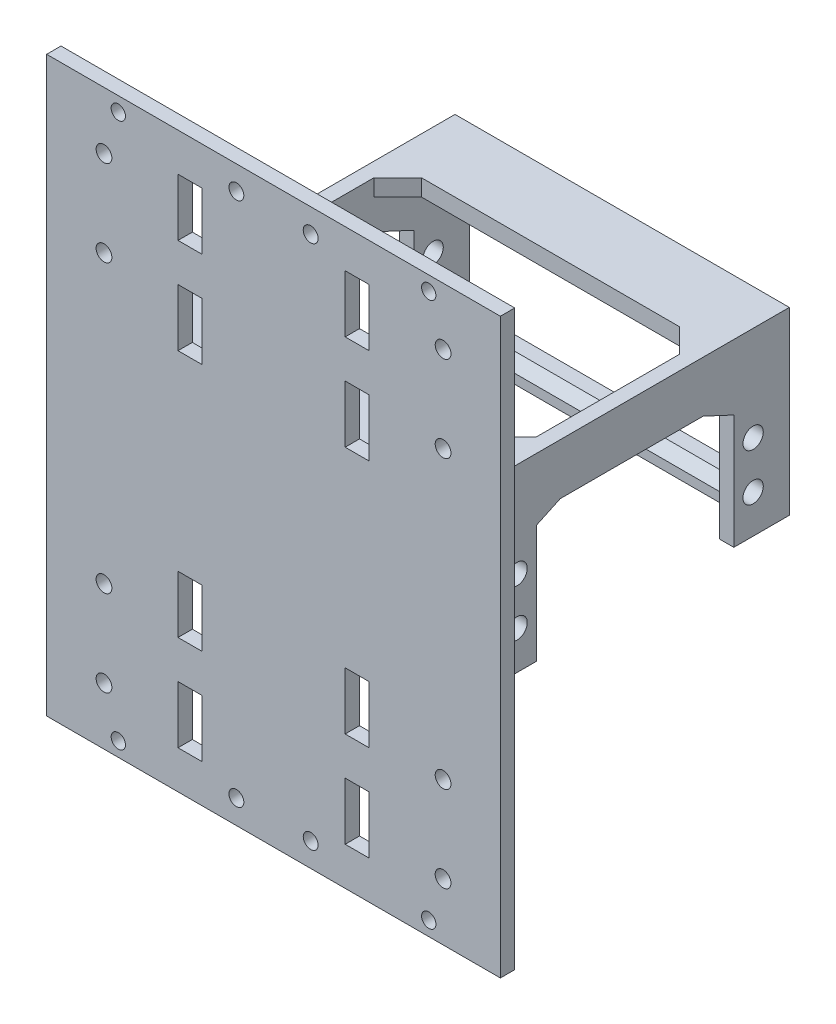
SolidWorks part; units mm, degrees
other "标注1"
sketch "草图14" plane through (-90, -59.2208, -73) normal (-0.775, -0.2253, -0.5905) x (0.6262, -0.4, -0.6693)
ref_plane "前视基准面" through (0, 0, 0) normal (0, 0, 1) x (1, 0, 0)
ref_plane "上视基准面" through (0, 0, 0) normal (0, 1, 0) x (1, 0, 0)
ref_plane "右视基准面" through (0, 0, 0) normal (1, 0, 0) x (0, 0, -1)
sketch "草图1" plane through (0, 0, 0) normal (0, 0, 1) x (1, 0, 0)
  line L0 (-47.5, 0) -> (47.5, 0) construction
  line L1 (-47.5, 60) -> (47.5, 60)
  line L2 (-47.5, 60) -> (-47.5, -60)
  line L3 (-47.5, -60) -> (47.5, -60)
  line L4 (47.5, 60) -> (47.5, -60)
  line L5 (0, 60) -> (0, -60) construction
  point P8 (0, 0)
  dimension "D1" = 120
  dimension "D2" = 95
extrude "凸台-拉伸1" add sketch "草图1" along normal blind 3 contours L2 L1 L4 L3
sketch "草图2" plane through (0, 0, 0) normal (0, 0, -1) x (-1, 0, 0)
  line L0 (-47.5, 0) -> (47.5, 0) construction
  line L1 (-47.5, 60) -> (-47.5, -60) construction
  line L2 (47.5, 60) -> (47.5, -60) construction
  line L3 (0, 60) -> (0, -60) construction
  line L4 (47.5, 60) -> (-47.5, 60) construction
  line L5 (47.5, -60) -> (-47.5, -60) construction
  line L6 (-35, -18.85) -> (-32, -18.85)
  line L7 (-35, 0) -> (-32, 0)
  line L8 (-35, -18.85) -> (-35, 18.85)
  line L9 (-35, 18.85) -> (-32, 18.85)
  line L10 (-32, -18.85) -> (-32, 18.85)
  line L11 (35, -18.85) -> (35, 18.85)
  line L12 (35, 18.85) -> (32, 18.85)
  line L13 (32, -18.85) -> (32, 18.85)
  line L14 (35, -18.85) -> (32, -18.85)
  dimension "D1" = 3
  dimension "D2" = 35
  dimension "D3" = 18.85
extrude "凸台-拉伸2" add sketch "草图2" along normal blind 70 contours L10 L9 L8 L6 | L11 L12 L13 L14
sketch "草图4" plane through (0, 0, 3) normal (0, 0, 1) x (1, 0, 0)
  line L0 (-47.5, 0) -> (47.5, 0) construction
  line L1 (-47.5, 60) -> (-32.5, 60) construction
  line L2 (-47.5, 60) -> (-47.5, 57) construction
  line L3 (-47.5, 57) -> (-32.5, 57) construction
  line L4 (-32.5, 60) -> (-32.5, 57) construction
  line L5 (-47.5, 60) -> (-47.5, -60) construction
  line L6 (47.5, 60) -> (47.5, -60) construction
  line L7 (0, 60) -> (0, -60) construction
  line L8 (-47.5, 60) -> (47.5, 60) construction
  line L9 (-47.5, -60) -> (47.5, -60) construction
  circle A0 centre (-32.5, 57) radius 1.5
  circle A1 centre (32.5, 57) radius 1.5
  circle A2 centre (32.5, -57) radius 1.5
  circle A3 centre (-32.5, -57) radius 1.5
  dimension "D3" = 3
  dimension "D1" = 3
  dimension "D2" = 15
extrude "切除-拉伸2" cut sketch "草图4" against normal blind 10
sketch "草图18" plane through (0, 0, 3) normal (0, 0, 1) x (1, 0, 0)
  line L0 (0, -40.15) -> (0, 40.15) construction
  line L1 (-20, -20) -> (-15, -20)
  line L2 (-20, -20) -> (-20, -32)
  line L3 (-20, -32) -> (-15, -32)
  line L4 (-15, -20) -> (-15, -32)
  line L5 (-20, -20) -> (-15, -32) construction
  line L6 (-20, -32) -> (-15, -20) construction
  line L7 (20, -32) -> (15, -20) construction
  line L8 (20, -20) -> (15, -32) construction
  line L9 (15, -20) -> (15, -32)
  line L10 (20, -32) -> (15, -32)
  line L11 (20, -20) -> (20, -32)
  line L12 (20, -20) -> (15, -20)
  line L13 (-20, -40) -> (-15, -40)
  line L14 (-20, -40) -> (-20, -52)
  line L15 (-20, -52) -> (-15, -52)
  line L16 (-15, -40) -> (-15, -52)
  line L17 (15, -40) -> (15, -52)
  line L18 (20, -52) -> (15, -52)
  line L19 (20, -40) -> (20, -52)
  line L20 (20, -40) -> (15, -40)
  line L21 (-20, -40) -> (-15, -52) construction
  line L22 (-20, -52) -> (-15, -40) construction
  line L23 (20, -52) -> (15, -40) construction
  line L24 (20, -40) -> (15, -52) construction
  line L25 (40.15, 0) -> (-40.15, 0) construction
  line L26 (20, 40) -> (15, 52) construction
  line L27 (20, 52) -> (15, 40) construction
  line L28 (-20, 52) -> (-15, 40) construction
  line L29 (-20, 40) -> (-15, 52) construction
  line L30 (20, 20) -> (15, 32) construction
  line L31 (20, 32) -> (15, 20) construction
  line L32 (-20, 32) -> (-15, 20) construction
  line L33 (-20, 20) -> (-15, 32) construction
  line L34 (20, 40) -> (15, 40)
  line L35 (20, 40) -> (20, 52)
  line L36 (20, 52) -> (15, 52)
  line L37 (15, 40) -> (15, 52)
  line L38 (-15, 40) -> (-15, 52)
  line L39 (-20, 52) -> (-15, 52)
  line L40 (-20, 40) -> (-20, 52)
  line L41 (-20, 40) -> (-15, 40)
  line L42 (20, 20) -> (15, 20)
  line L43 (20, 20) -> (20, 32)
  line L44 (20, 32) -> (15, 32)
  line L45 (15, 20) -> (15, 32)
  line L46 (-15, 20) -> (-15, 32)
  line L47 (-20, 32) -> (-15, 32)
  line L48 (-20, 20) -> (-20, 32)
  line L49 (-20, 20) -> (-15, 20)
  point P0 (-17.5, -26)
  point P12 (17.5, -26)
  point P14 (-17.5, -46)
  point P23 (17.5, -46)
  point P41 (17.5, 46)
  point P42 (-17.5, 46)
  point P43 (17.5, 26)
  point P44 (-17.5, 26)
  dimension "D1" = 15
  dimension "D2" = 20
  dimension "D3" = 5
  dimension "D4" = 12
  dimension "D5" = 2
extrude "切除-拉伸5" cut sketch "草图18" against normal blind 20
sketch "草图21" plane through (0, 0, 3) normal (0, 0, 1) x (1, 0, 0)
  line L1 (-47.5, 60) -> (-47.5, -60) construction
  line L2 (-47.5, -60) -> (47.5, -60) construction
  line L3 (0, -40.15) -> (0, 40.15) construction
  line L4 (40.15, 0) -> (-40.15, 0) construction
  circle A0 centre (-35.5, -48) radius 1.65
  circle A1 centre (-35.5, -30) radius 1.65
  circle A4 centre (35.5, -30) radius 1.65
  circle A5 centre (35.5, -48) radius 1.65
  circle A6 centre (35.5, 48) radius 1.65
  circle A7 centre (35.5, 30) radius 1.65
  circle A10 centre (-35.5, 30) radius 1.65
  circle A11 centre (-35.5, 48) radius 1.65
  circle A12 centre (-35.5, -12) radius 1.65 [skipped]
  dimension "D1" = 3.3
  dimension "D2" = 12
  dimension "D3" = 12
  dimension "D4" = 3
extrude "切除-拉伸6" cut sketch "草图21" against normal blind 10
sketch "草图22" plane through (0, 0, 3) normal (0, 0, 1) x (1, 0, 0)
  line L0 (0, -40.15) -> (0, 40.15) construction
  line L1 (-47.5, -60) -> (47.5, -60) construction
  line L2 (40.15, 0) -> (-40.15, 0) construction
  circle A0 centre (-7.78, -55) radius 1.56
  circle A1 centre (7.78, -55) radius 1.56
  circle A2 centre (7.78, 55) radius 1.56
  circle A3 centre (-7.78, 55) radius 1.56
  dimension "D1" = 3.12
  dimension "D2" = 5
  dimension "D3" = 15.56
extrude "切除-拉伸7" cut sketch "草图22" against normal blind 10
sketch "草图3" plane through (35, 0, 0) normal (1, 0, 0) x (0, 0, -1)
  line L0 (0, 60) -> (0, -60) construction
  line L13 (70, -18.85) -> (0, -18.85) construction
  circle A0 centre (13, -1) radius 2.125
  circle A1 centre (13, -10.85) radius 2.125
  circle A2 centre (62.42, -1) radius 2.125
  circle A3 centre (62.42, -10.85) radius 2.125
  dimension "D11" = 4.25
  dimension "D2" = 4.25
  dimension "D3" = 9.85
  dimension "D4" = 8
  dimension "D6" = 13
  dimension "D5" = 2
extrude "切除-拉伸8" cut sketch "草图3" against normal blind 80
sketch "草图23" plane through (35, 0, 0) normal (1, 0, 0) x (0, 0, -1)
  line L0 (13, -10.85) -> (62.42, -10.85) construction
  line L2 (17.0421, 8.15) -> (17.0421, -18.85)
  line L3 (58.3779, 8.15) -> (58.3779, -18.85)
  line L4 (17.0421, -18.85) -> (58.3779, -18.85)
  line L7 (70, -18.85) -> (0, -18.85) construction
  line L8 (17.0421, 8.15) -> (58.3779, 8.15)
  point P5 (37.71, -10.85)
  dimension "D1" = 27
extrude "切除-拉伸9" cut sketch "草图23" against normal blind 80
chamfer "倒角4" distance 3 angle 65 2 edges at (33.5, 8.15, -58.3779) (-33.5, 8.15, -58.3779)
chamfer "倒角5" distance 5 angle 25 2 edges at (33.5, 8.15, -17.0421) (-33.5, 8.15, -17.0421)
sketch "草图24" plane through (-32, 0, 0) normal (1, 0, 0) x (0, 0, -1)
  line L1 (0, 18.85) -> (15, 18.85)
  line L2 (0, 18.85) -> (0, 15.35)
  line L3 (0, 15.35) -> (15, 15.35)
  line L4 (15, 18.85) -> (15, 15.35)
  line L5 (70, 18.85) -> (55, 18.85)
  line L6 (70, 18.85) -> (70, 15.35)
  line L7 (70, 15.35) -> (55, 15.35)
  line L8 (55, 18.85) -> (55, 15.35)
  dimension "D1" = 3.5
  dimension "D2" = 15
  dimension "D3" = 15
extrude "凸台-拉伸3" add sketch "草图24" along normal up to surface (64 mm away) up to face at (32, -10.85, -64.545)
chamfer "倒角7" distance 5 angle 45 4 edges at (32, 17.1, -55) (-32, 17.1, -55) (-32, 17.1, -15) (32, 17.1, -15)
sketch "草图26" plane through (0, 0, 0) normal (0, 0, -1) x (-1, 0, 0)
  line L0 (32, -18.85) -> (32, 15.35) construction
  line L1 (-32, -18.85) -> (32, -18.85)
  line L2 (-32, -18.85) -> (-32, -14.85)
  line L3 (-32, -14.85) -> (32, -14.85)
  line L4 (32, -18.85) -> (32, -14.85)
  dimension "D1" = 4
extrude "凸台-拉伸5" add sketch "草图26" along normal blind 8
sketch "草图5" plane through (0, 0, -70) normal (0, 0, -1) x (-1, 0, 0)
  line L7 (-32, -14.85) -> (32, -14.85)
  line L10 (-32, -14.85) -> (-32, -18.85)
  line L11 (-32, -18.85) -> (32, -18.85)
  line L12 (32, -14.85) -> (32, -18.85)
extrude "凸台-拉伸6" add sketch "草图5" against normal blind 5
chamfer "倒角9" distance 2 angle 45 1 edges at (0, -14.85, -65)
